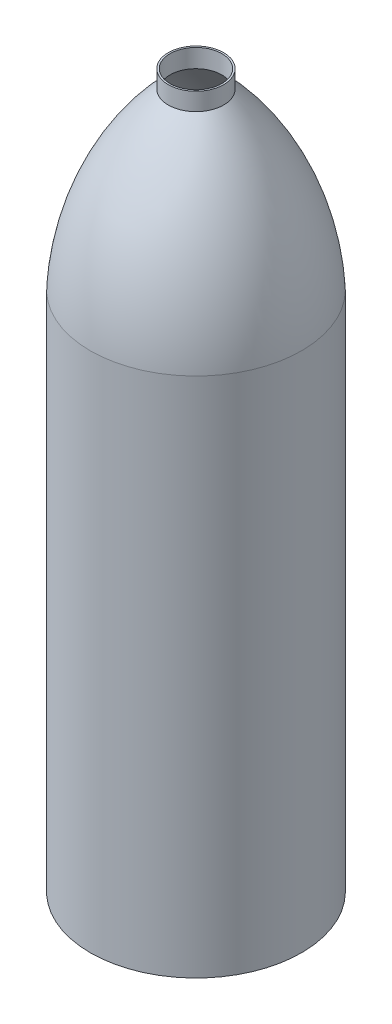
SolidWorks part; units mm, degrees
ref_plane "Front Plane" through (0, 0, 0) normal (0, 0, 1) x (1, 0, 0)
ref_plane "Top Plane" through (0, 0, 0) normal (0, 1, 0) x (1, 0, 0)
ref_plane "Right Plane" through (0, 0, 0) normal (1, 0, 0) x (0, 0, -1)
sketch "Sketch8" plane through (0, 0, 0) normal (0, 0, 1) x (1, 0, 0)
  line L0 (0, 434.7398) -> (0, -62.9788) construction
  line L1 (0, -44.1577) -> (-60, -44.1577)
  line L2 (-60, -44.1577) -> (-60, 255.8423)
  line L3 (0, -45.1577) -> (-61, -45.1577)
  line L4 (-15, 355.8423) -> (-15, 365.4734)
  line L5 (-16, 366.4734) -> (-15, 366.4734)
  line L6 (-61, -45.1577) -> (-61, 255.8697)
  line L7 (-16, 356.259) -> (-16, 366.4734)
  line L8 (-15, 366.4734) -> (-15, 365.4734)
  line L9 (-16, 366.4734) -> (0, 366.4734) construction
  line L10 (-15, 365.4734) -> (0, 365.4734) construction
  line L11 (0, -44.1577) -> (0, -45.1577)
  arc A0 (-15, 355.8423) -> (-60, 255.8423) centre (92.1525, 247.4987) ccw
  arc A1 (-16, 356.259) -> (-61, 255.8697) centre (92.1525, 247.4987) ccw
  dimension "D1" = 60
  dimension "D2" = 300
  dimension "D3" = 100
  dimension "D5" = 1
revolve "Revolve1" add sketch "Sketch8" angle 360 about L0
